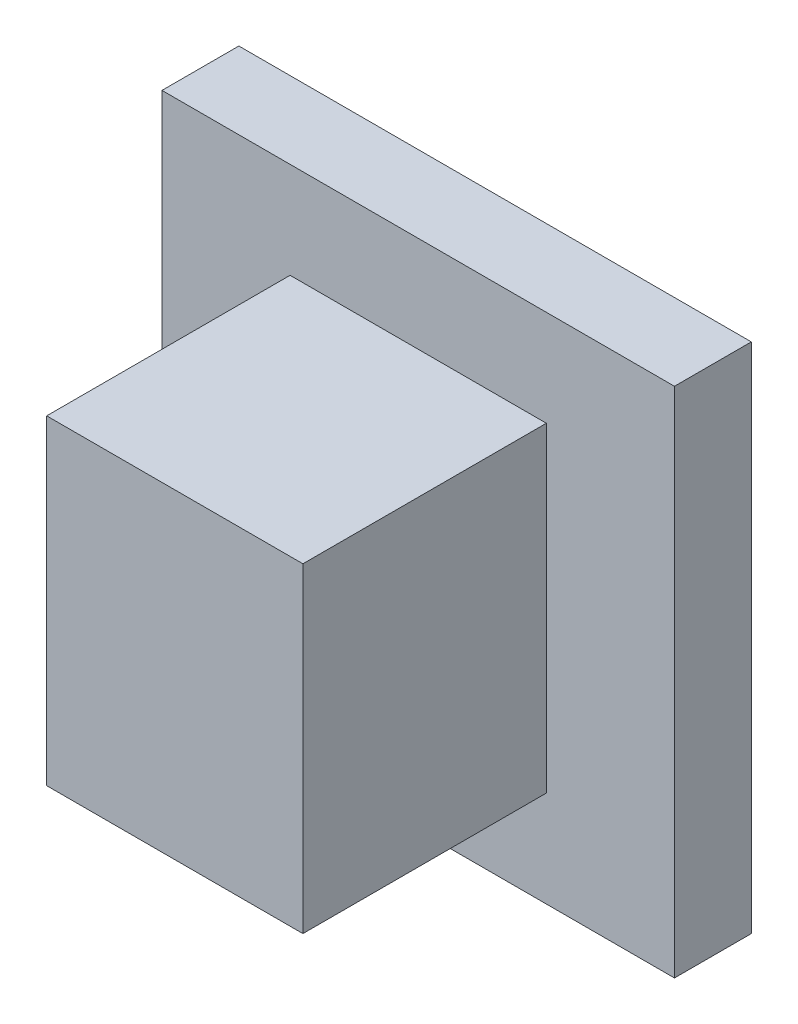
SolidWorks part; units mm, degrees
ref_plane "前视基准面" through (0, 0, 0) normal (0, 0, 1) x (1, 0, 0)
ref_plane "上视基准面" through (0, 0, 0) normal (0, 1, 0) x (1, 0, 0)
ref_plane "右视基准面" through (0, 0, 0) normal (1, 0, 0) x (0, 0, -1)
other "Configuration Table"
sketch "草图1" plane through (0, 0, 0) normal (0, 0, 1) x (1, 0, 0)
  line L1 (0, 0) -> (2, 0)
  line L2 (0, 0) -> (0, 3)
  line L3 (0, 3) -> (2, 3)
  line L4 (2, 0) -> (2, 3)
  line L5 (-1, 4) -> (3, 4)
  line L6 (-1, 4) -> (-1, -1)
  line L7 (-1, -1) -> (3, -1)
  line L8 (3, 4) -> (3, -1)
  dimension "D1" = 2
  dimension "D2" = 3
  dimension "D3" = 1
  dimension "D4" = 1
  dimension "D5" = 1
  dimension "D6" = 1
extrude "凸台-拉伸1" add sketch "草图1" along normal blind 4
sketch "草图2" plane through (0, 0, 0) normal (0, 0, -1) x (-1, 0, 0)
  line L0 (-3, 4) -> (1, 4)
  line L1 (1, 4) -> (1, -1)
  line L2 (1, -1) -> (-3, -1)
  line L3 (-3, -1) -> (-3, -2.5)
  line L4 (-3, -2.5) -> (3, -2.5)
  line L5 (3, -2.5) -> (3, 5.5)
  line L6 (3, 5.5) -> (-3, 5.5)
  line L7 (-3, 5.5) -> (-3, 4)
  dimension "D1" = 1.5
  dimension "D2" = 2
  dimension "D3" = 1.5
extrude "凸台-拉伸2" add sketch "草图2" against normal blind 1.2
sketch "草图3" plane through (0, 0, 4) normal (0, 0, 1) x (1, 0, 0)
  line L4 (-1, 4) -> (-1, -1)
  line L5 (-1, -1) -> (3, -1)
  line L6 (3, -1) -> (3, 4)
  line L7 (3, 4) -> (-1, 4)
  line L8 (-1, 4) -> (-1, -1)
  line L9 (-1, -1) -> (3, -1)
  line L10 (3, -1) -> (3, 4)
  line L11 (3, 4) -> (-1, 4)
  dimension "D1" = 0
extrude "凸台-拉伸3" add sketch "草图3" along normal blind 1
sketch "草图4" plane through (0, 0, 1.2) normal (0, 0, 1) x (1, 0, 0)
  line L0 (3, 5.5) -> (5, 5.5)
  line L1 (5, 5.5) -> (5, -2.5)
  line L2 (5, -2.5) -> (3, -2.5)
  line L4 (3, -1) -> (3, 4) construction
  line L5 (3, 5.5) -> (3, -2.5)
  dimension "D1" = 2
extrude "凸台-拉伸4" add sketch "草图4" against normal up to surface (1.2 mm away) up to face at (0, 1.5, 0)
